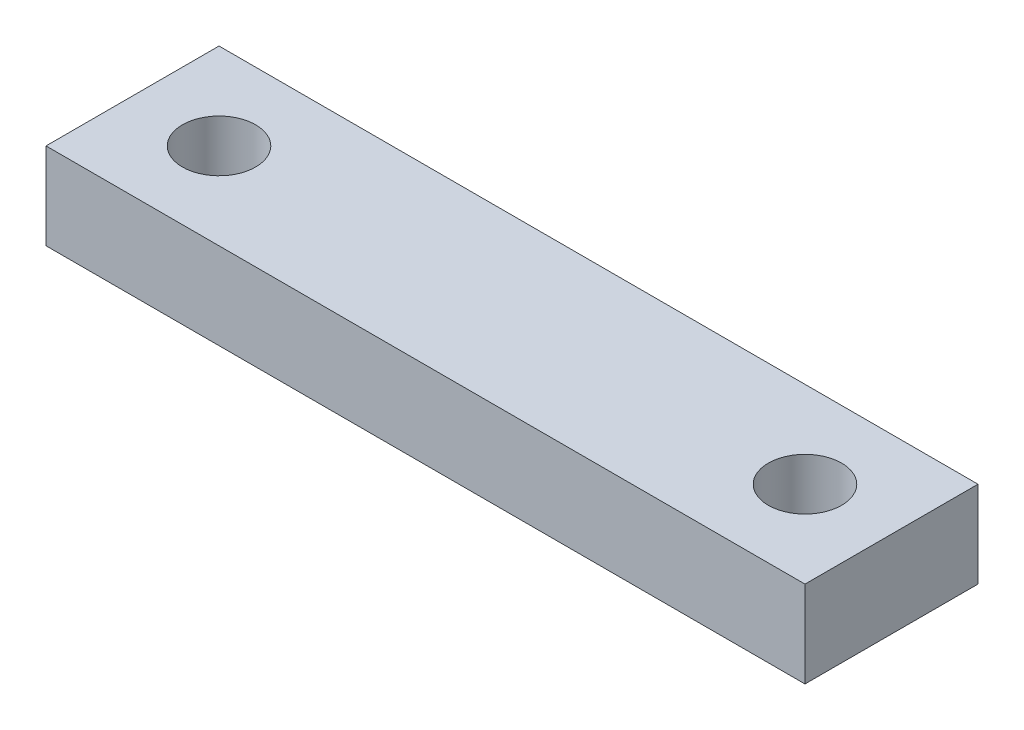
SolidWorks part; units mm, degrees
ref_plane "Front Plane" through (0, 0, 0) normal (0, 0, 1) x (1, 0, 0)
ref_plane "Top Plane" through (0, 0, 0) normal (0, 1, 0) x (1, 0, 0)
ref_plane "Right Plane" through (0, 0, 0) normal (1, 0, 0) x (0, 0, -1)
sketch "Sketch1" plane through (0, 0, 0) normal (0, 0, 1) x (1, 0, 0)
  line L1 (-215.2134, 20.1412) -> (47.9866, 20.1412)
  line L2 (-215.2134, 20.1412) -> (-215.2134, -9.8588)
  line L3 (-215.2134, -9.8588) -> (47.9866, -9.8588)
  line L4 (47.9866, 20.1412) -> (47.9866, -9.8588)
  dimension "D1" = 263.2
  dimension "D2" = 30
extrude "Boss-Extrude1" add sketch "Sketch1" along normal blind 60
sketch "Sketch2" plane through (0, 20.1412, 0) normal (0, 1, 0) x (1, 0, 0)
  line L0 (47.9866, -60) -> (47.9866, 0) construction
  line L2 (-215.2134, -60) -> (-215.2134, 0) construction
  circle A0 centre (17.9866, -30) radius 12.7
  circle A1 centre (-185.2134, -30) radius 12.7
  dimension "D1" = 25.4
  dimension "D2" = 30
  dimension "D3" = 25.4
  dimension "D5" = 30
  dimension "D4" = 203.2
extrude "Cut-Extrude1" cut sketch "Sketch2" against normal through all
sketch "Sketch3" plane through (0, 20.1412, 0) normal (0, 1, 0) x (1, 0, 0)
  circle A1 centre (-185.2134, -30) radius 24.5462
  circle A2 centre (19.3869, -30) radius 25.1822
